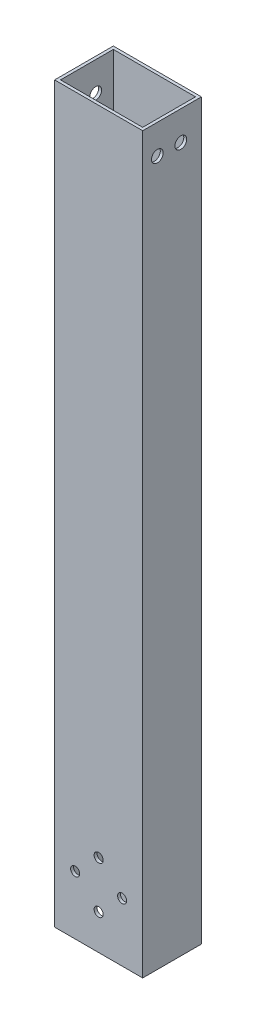
SolidWorks part; units mm, degrees
ref_plane "前视基准面" through (0, 0, 0) normal (0, 0, 1) x (1, 0, 0)
ref_plane "上视基准面" through (0, 0, 0) normal (0, 1, 0) x (1, 0, 0)
ref_plane "右视基准面" through (0, 0, 0) normal (1, 0, 0) x (0, 0, -1)
other "Configuration Table"
sketch "草图1" plane through (0, 0, 0) normal (0, 1, 0) x (1, 0, 0)
  line L1 (-15, -10) -> (15, -10)
  line L2 (-15, -10) -> (-15, 10)
  line L3 (-15, 10) -> (15, 10)
  line L4 (15, -10) -> (15, 10)
  line L5 (0, 10) -> (0, -10) construction
  line L6 (-15, 0) -> (15, 0) construction
  line L7 (-14, -9) -> (14, -9)
  line L8 (-14, -9) -> (-14, 9)
  line L9 (-14, 9) -> (14, 9)
  line L10 (14, -9) -> (14, 9)
  line L11 (0, 9) -> (0, -9) construction
  line L12 (-14, 0) -> (14, 0) construction
  point P0 (0, 0)
  point P4 (0, 0)
  dimension "D1" = 30
  dimension "D2" = 20
  dimension "D3" = 1
  dimension "D4" = 1
extrude "凸台-拉伸1" add sketch "草图1" along normal blind 250
sketch "草图2" plane through (0, 0, 0) normal (0, 0, 1) x (1, 0, 0)
  line L0 (0, -46.283) -> (0, 306.1037) construction
  line L1 (-83.5307, 20) -> (87.1925, 20) construction
  line L2 (0, 20) -> (0, 28) construction
  circle A0 centre (0, 28) radius 1.55
  circle A1 centre (8, 20) radius 1.55
  circle A2 centre (0, 12) radius 1.55
  circle A3 centre (-8, 20) radius 1.55
  point P5 (0, 17)
  point P7 (0, 20)
  point P8 (0, 0)
  point P9 (0, 0)
  dimension "D2" = 3.1
  dimension "D1" = 20
  dimension "D4" = 8
  dimension "D3" = 4
extrude "切除-拉伸1" cut sketch "草图2" against normal through all both and the other way through all
sketch "草图3" plane through (0, 0, 0) normal (1, 0, 0) x (0, 0, -1)
  line L0 (-82.4991, 240) -> (85.7164, 240) construction
  line L1 (-10, 250) -> (10, 250) construction
  line L2 (-10, 250) -> (-10, 0) construction
  circle A0 centre (-5, 240) radius 2
  circle A1 centre (3, 240) radius 2
  dimension "D4" = 4
  dimension "D1" = 10
  dimension "D2" = 5
  dimension "D3" = 8
extrude "切除-拉伸2" cut sketch "草图3" against normal through all both and the other way through all
